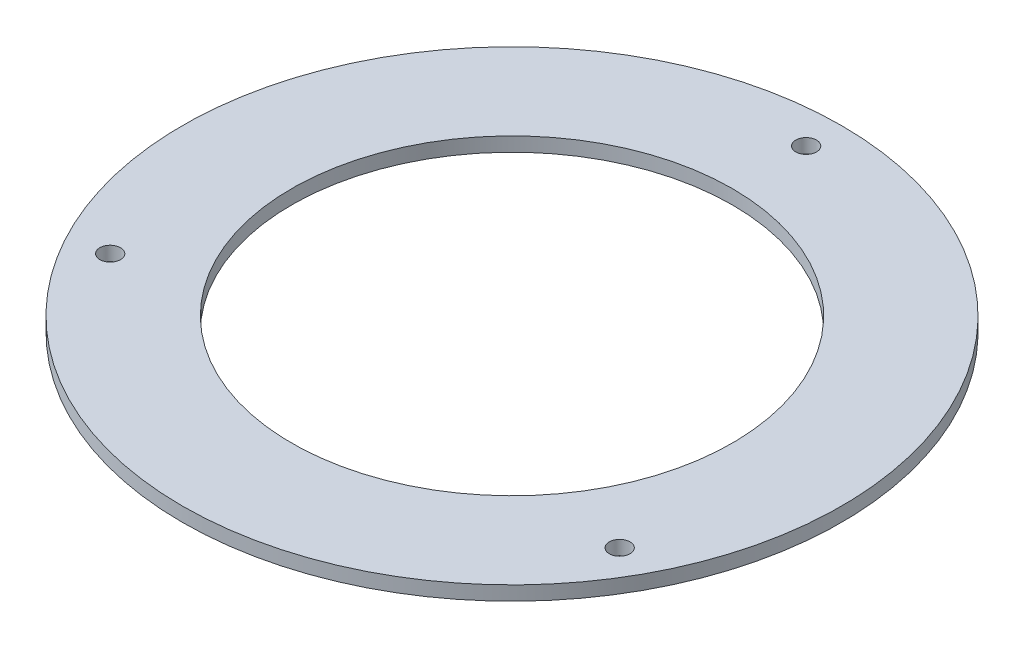
SolidWorks part; units mm, degrees
ref_plane "Front Plane" through (0, 0, 0) normal (0, 0, 1) x (1, 0, 0)
ref_plane "Top Plane" through (0, 0, 0) normal (0, 1, 0) x (1, 0, 0)
ref_plane "Right Plane" through (0, 0, 0) normal (1, 0, 0) x (0, 0, -1)
sketch "Sketch1" plane through (0, 0, 0) normal (0, 1, 0) x (1, 0, 0)
  line L0 (0, 0) -> (0, 76.835) construction
  line L1 (0, 0) -> (0, 68.58) construction
  circle A0 centre (0, 0) radius 76.835
  circle A1 centre (0, 0) radius 51.3842
  circle A2 centre (0, 68.58) radius 2.413
  circle A3 centre (59.392, -34.29) radius 2.413
  circle A4 centre (0, 0) radius 76.835
  circle A5 centre (-59.392, -34.29) radius 2.413
  circle A6 centre (0, 0) radius 76.835
  dimension "D1" = 153.67
  dimension "D2" = 102.7684
  dimension "D3" = 4.826
  dimension "D6" = 68.58
  dimension "D5" = 3
extrude "Boss-Extrude1" add sketch "Sketch1" along normal blind 3.302 contours A0 A5 A3 A2 A1
